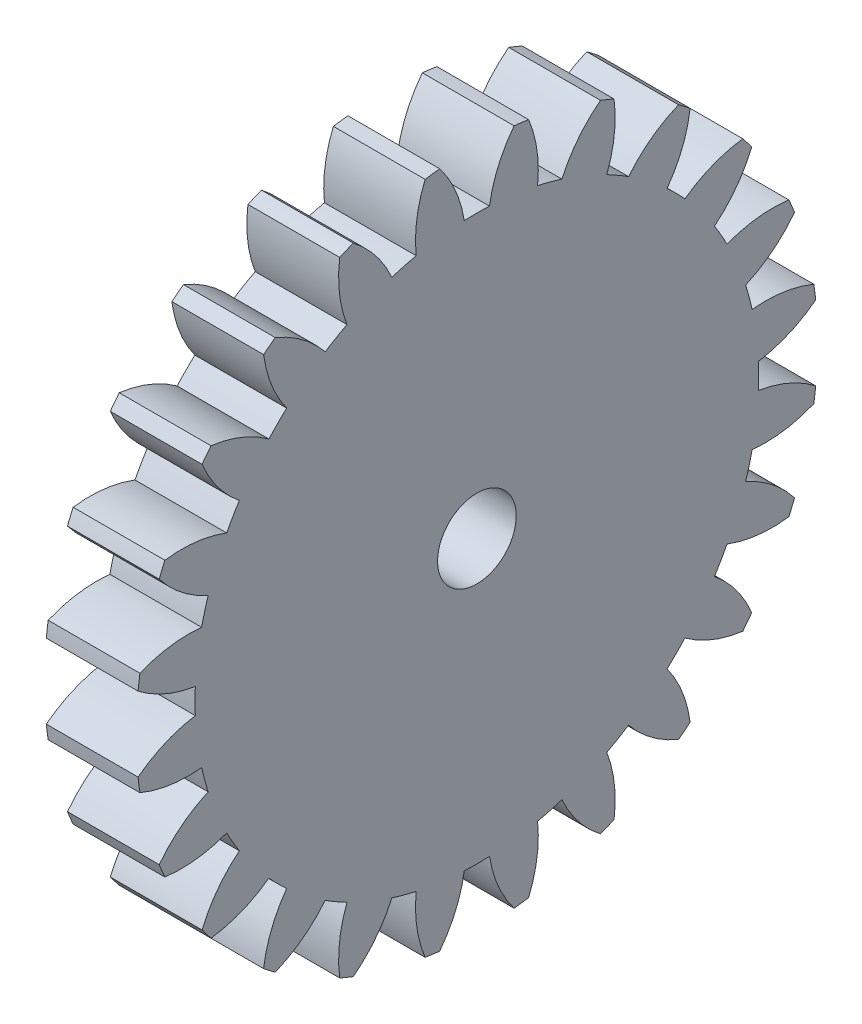
SolidWorks part; units mm, degrees
ref_plane "Plane1" through (0, 0, 0) normal (0, 0, 1) x (1, 0, 0)
ref_plane "Plane2" through (0, 0, 0) normal (0, 1, 0) x (1, 0, 0)
ref_plane "Plane3" through (0, 0, 0) normal (1, 0, 0) x (0, 0, -1)
sketch "HoldingSke" plane through (0, 0, 0) normal (0, 1, 0) x (1, 0, 0)
  line L0 (0, 0) -> (92.8162, -41.3244)
  line L1 (-15, 0) -> (100, 0) construction
  line L2 (0, 0) -> (-2.1039, 2.3779)
  line L3 (0, 0) -> (-11.863, 4.5341)
  line L4 (0, 0) -> (7.8894, 3.5126)
  line L5 (0, 0) -> (-23.7986, -8.8762)
  line L6 (0, 0) -> (-18.4237, -12.4305)
  line L7 (-2.1039, 2.3779) -> (3.3635, 27.1825)
  line L8 (-76.2, 54.61) -> (-54.61, 54.61)
  line L9 (-71.009, 38.7566) -> (-53.1078, 45.2721)
  line L10 (-76.2, 71.12) -> (104.1128, 71.12)
  line L11 (0, 0) -> (-22.225, 0)
  line L12 (-76.2, 101.6) -> (-75.9714, 101.6)
  line L13 (24.9733, 27.94) -> (52.9518, 28.4284)
  line L14 (24.9733, 27.94) -> (24.9746, 27.94)
  line L15 (24.9733, 27.94) -> (100.4006, 29.5858)
  circle A0 centre (0, 0) radius 9.525
  circle A1 centre (0, 0) radius 12.7
  circle A2 centre (0, 0) radius 12.7
  circle A3 centre (0, 0) radius 9.525
  dimension "MHD" = 25.4
  dimension "Hub_dia" = 25.4
  dimension "Bore" = 19.05
  dimension "MBD" = 19.05
  dimension "Num_teeth" = 24
  dimension "Pitch" = 101.6
  dimension "Overall_len" = 25.4
  dimension "Show_teeth" = 24
  dimension "Thickness" = 22.225
  dimension "OAL" = 25.4001
  dimension "T_dim" = 21.59
  dimension "Ap" = 20
  dimension "H" = 19.05
  dimension "Pitch_radius" = 180.3128
  dimension "Width" = 22.225
  dimension "Backlash" = 0.2286
  dimension "Addendum_fac" = 1
  dimension "Dedendum_fac" = 1.25
  dimension "Clearance_fac" = 0.25
  dimension "Dedendum_add" = 0.0013
sketch "BasProSke" plane through (0, 0, 0) normal (0, 1, 0) x (1, 0, 0)
  line L0 (-10, 0) -> (60, 0) construction
  line L1 (0, 0) -> (0, 82.55)
  line L2 (0, 0) -> (22.225, 0)
  line L3 (22.225, 0) -> (22.225, 82.55)
  line L4 (22.225, 82.55) -> (0, 82.55)
  dimension "Thickness" = 22.225
  dimension "Diameter" = 165.1
revolve "Base-Revolve" add sketch "BasProSke" angle 360 about L0
sketch "TooCutSke" plane through (0, 0, 0) normal (1, 0, 0) x (0, 0, -1)
  line L1 (0, 0) -> (0, 107) construction
  line L2 (0, 0) -> (-5.3836, 76.0096) construction
  line L3 (0, 0) -> (-19.8562, 150.8226) construction
  line L4 (-5.3836, 76.0096) -> (-9.9281, 75.4113) construction
  arc A0 (3.0508, 68.193) -> (-3.0508, 68.193) centre (0, 0) ccw
  arc A1 (9.0282, 82.0804) -> (-9.0282, 82.0804) centre (0, 0) ccw
  circle A2 centre (0, 0) radius 76.2 construction
  circle A3 centre (0, 0) radius 71.6046 construction
  arc A4 (-3.0508, 68.193) -> (-9.0282, 82.0804) centre (-33.1615, 63.4628) ccw
  arc A5 (9.0282, 82.0804) -> (3.0508, 68.193) centre (33.1615, 63.4628) ccw
  dimension "Root_dia" = 136.5225
  dimension "Overcut_dia" = 165.1508
  dimension "Pitch_dia" = 152.4
  dimension "Base_dia" = 143.2092
  dimension "Flank_rad" = 30.48
  dimension "Half_ang" = 7.5
  dimension "Half_CT" = 4.5837
extrude "ToothCut" cut sketch "TooCutSke" along normal through all
fillet "Breaks" [suppressed] radius 0.127
fillet "RootFillets" [suppressed] radius 1.5888
pattern_circular "TeethCuts" count 24 every 15 about axis through (-10, 0, 0) along (1, 0, 0) of "ToothCut", "RootFillets", "Breaks"
sketch "HubNeaOneSke" plane through (0, 0, 0) normal (-1, 0, 0) x (0, 0, 1)
  circle A0 centre (0, 0) radius 12.7
  dimension "Diameter" = 25.4
extrude "HubNearOne" [suppressed] add sketch "HubNeaOneSke" along normal blind 3.1751
sketch "HubNeaBotSke" plane through (0, 0, 0) normal (-1, 0, 0) x (0, 0, 1)
  circle A0 centre (0, 0) radius 12.7
  dimension "Diameter" = 25.4
extrude "HubNearBoth" [suppressed] add sketch "HubNeaBotSke" along normal blind 1.5875
ref_plane "FarPln" through (22.225, 0, 0) normal (1, 0, 0) x (0, 0, -1)
sketch "HubFarSke" plane through (22.225, 0, 0) normal (1, 0, 0) x (0, 0, -1)
  circle A0 centre (0, 0) radius 12.7
  dimension "Diameter" = 25.4
extrude "HubFar" [suppressed] add sketch "HubFarSke" along normal blind 1.5875
sketch "BorSke" plane through (0, 0, 0) normal (1, 0, 0) x (0, 0, -1)
  circle A0 centre (0, 0) radius 9.525
  dimension "Diameter" = 19.05
extrude "Bore" cut sketch "BorSke" along normal mid plane 50.8001
sketch "KeySke" plane through (0, 0, 0) normal (1, 0, 0) x (0, 0, -1)
  line L0 (-3.175, 0) -> (-3.175, 12.065)
  line L1 (-3.175, 12.065) -> (3.175, 12.065)
  line L2 (3.175, 12.065) -> (3.175, 0)
  line L3 (0, 0) -> (0, 34) construction
  line L4 (-3.175, 0) -> (3.175, 0)
  dimension "Offset" = 12.065
  dimension "Width" = 6.35
extrude "Keyway" [suppressed] cut sketch "KeySke" along normal mid plane 50.8001
pattern_circular "Keyway2" [suppressed] count 2 every 90 about axis through (-10, 0, 0) along (1, 0, 0)
equation "' \"Pitch@HoldingSke\" = 4"
equation "' \"Num_teeth@HoldingSke\" = 12"
equation "' \"Ap@HoldingSke\" =  20"
equation "' \"Ap@HoldingSke\" = 20"
equation "' \"Width@HoldingSke\" = 0.5"
equation "' \"Hub_dia@HoldingSke\"= 1"
equation "' \"Hub_dia@HoldingSke\" = 1"
equation "' \"Overall_len@HoldingSke\" = 1.0"
equation "' \"Bore@HoldingSke\" = 0.75"
equation "' \"T_dim@HoldingSke\" = 0.85"
equation "' \"Width@KeySke\" = 0.25"
equation "' \"Show_teeth@HoldingSke\" = 13"
equation "' \"Backlash@HoldingSke\" = 0.009"
equation "' \"Addendum_fac@HoldingSke\" = 1.0"
equation "' \"Dedendum_fac@HoldingSke\" = 1.25"
equation "' \"Dedendum_add@HoldingSke\" = 0.00005"
equation "' \"Clearance_fac@HoldingSke\" = 0.25"
equation "' \"Pitch@HoldingSke\" = 0.5"
equation "' \"Num_teeth@HoldingSke\" = 23"
equation "' \"Show_teeth@HoldingSke\" = 23"
equation "' \"Backlash@HoldingSke\" = 0.0375"
equation "\"Overcut_dia@TooCutSke\" = (\"Num_teeth@HoldingSke\" + 2 * \"Addendum_fac@HoldingSke\") / \"Pitch@HoldingSke\" + 0.002"
equation "\"Pitch_dia@TooCutSke\" = \"Num_teeth@HoldingSke\" / \"Pitch@HoldingSke\""
equation "\"Base_dia@TooCutSke\" = \"Num_teeth@HoldingSke\" / \"Pitch@HoldingSke\" * cos((\"Ap@HoldingSke\"  * 3.14159265 / 180))"
equation "\"Root_dia@TooCutSke\" = (\"Num_teeth@HoldingSke\" + 2) / \"Pitch@HoldingSke\" - 2 * (\"Addendum_fac@HoldingSke\" + \"Dedendum_fac@HoldingSke\") / \"Pitch@HoldingSke\" - \"Dedendum_add@HoldingSke\" * 2"
equation "\"Half_ang@TooCutSke\" = 180 / \"Num_teeth@HoldingSke\""
equation "\"Half_CT@TooCutSke\" = \"Num_teeth@HoldingSke\" / \"Pitch@HoldingSke\" * sin((3.14159265 / 2 / \"Num_teeth@HoldingSke\")) / 2 - 7 * \"Backlash@HoldingSke\" / 4"
equation "\"Flank_rad@TooCutSke\" = \"Num_teeth@HoldingSke\" / \"Pitch@HoldingSke\" / 5"
equation "\"Radius@RootFillets\" = \"Clearance_fac@HoldingSke\" / \"Pitch@HoldingSke\" + \"Dedendum_add@HoldingSke\""
equation "\"Break_rad@Breaks\" = 0.02 / \"Pitch@HoldingSke\""
equation "\"Thickness@HoldingSke\" = \"Width@HoldingSke\""
equation "\"OAL@HoldingSke\" = \"Thickness@HoldingSke\""
equation "\"MHD@HoldingSke\" = (\"Num_teeth@HoldingSke\" + 2) / \"Pitch@HoldingSke\" - 2 * (\"Addendum_fac@HoldingSke\" + \"Dedendum_fac@HoldingSke\")  / \"Pitch@HoldingSke\" - \"Dedendum_add@HoldingSke\" * 2"
equation "\"MBD@HoldingSke\" = (\"Num_teeth@HoldingSke\" + 2) / \"Pitch@HoldingSke\" - 2 * (\"Addendum_fac@HoldingSke\" + \"Dedendum_fac@HoldingSke\")  / \"Pitch@HoldingSke\" - \"Dedendum_add@HoldingSke\" * 2 - 0.002"
equation "\"MHD@HoldingSke\" = ((sgn( \"MHD@HoldingSke\" - \"Hub_dia@HoldingSke\" )-1)*( \"MHD@HoldingSke\" - \"Hub_dia@HoldingSke\" ))/-2+ \"Hub_dia@HoldingSke\""
equation "\"MBD@HoldingSke\" = ((sgn( \"MBD@HoldingSke\" - \"Bore@HoldingSke\" )-1)*( \"MBD@HoldingSke\" - \"Bore@HoldingSke\" ))/-2+ \"Bore@HoldingSke\""
equation "\"OAL@HoldingSke\" = ((sgn( \"OAL@HoldingSke\" - \"Overall_len@HoldingSke\" )+1)*( \"OAL@HoldingSke\" - \"Overall_len@HoldingSke\" ))/2 + \"Overall_len@HoldingSke\" + 0.000002"
equation "\"Num_teeth@TeethCuts\" = int( \"Show_teeth@HoldingSke\" ) + 1"
equation "\"Num_teeth@TeethCuts\" = ((sgn( \"Num_teeth@TeethCuts\" - \"Num_teeth@HoldingSke\" )-1)*( \"Num_teeth@TeethCuts\" - \"Num_teeth@HoldingSke\" ))/-2+ \"Num_teeth@HoldingSke\""
equation "\"Num_teeth@TeethCuts\" = ((sgn( \"Num_teeth@TeethCuts\" - 2.0)+1)*( \"Num_teeth@TeethCuts\" - 2.0))/2 +2.0"
equation "\"Angle@TeethCuts\" = 360.0 / \"Num_teeth@HoldingSke\""
equation "\"Diameter@BasProSke\" = (\"Num_teeth@HoldingSke\" + 2 * \"Addendum_fac@HoldingSke\") / \"Pitch@HoldingSke\""
equation "\"Thickness@BasProSke\"  = \"Thickness@HoldingSke\""
equation "' \"Fillet_rad@BasProSke\" =  \"Thickness@HoldingSke\" * 0.05"
equation "' \"Fillet_rad@BasProSke\" = \"Thickness@HoldingSke\" * 0.05"
equation "\"MHD@HoldingSke\" = ((sgn( \"MHD@HoldingSke\" - \"Root_dia@TooCutSke\" )-1)*( \"MHD@HoldingSke\" - \"Root_dia@TooCutSke\" ))/-2+ \"Root_dia@TooCutSke\""
equation "\"Diameter@HubNeaOneSke\" = \"MHD@HoldingSke\""
equation "\"Length@HubNearOne\" = \"OAL@HoldingSke\" - \"Thickness@BasProSke\""
equation "\"Diameter@HubNeaBotSke\" = \"MHD@HoldingSke\""
equation "\"Length@HubNearBoth\" = ( \"OAL@HoldingSke\" - \"Thickness@BasProSke\" ) / 2.0"
equation "\"Thickness@FarPln\" = \"Thickness@BasProSke\""
equation "\"Diameter@HubFarSke\" = \"MHD@HoldingSke\""
equation "\"Length@HubFar\" = ( \"OAL@HoldingSke\" - \"Thickness@BasProSke\" ) / 2.0"
equation "\"Diameter@BorSke\" = \"MBD@HoldingSke\""
equation "\"D1@Bore\" = \"OAL@HoldingSke\" * 2.0"
equation "\"D1@Keyway\" = \"OAL@HoldingSke\" * 2.0"
equation "\"Offset@KeySke\" = \"T_dim@HoldingSke\" - \"MBD@HoldingSke\" / 2.0"
